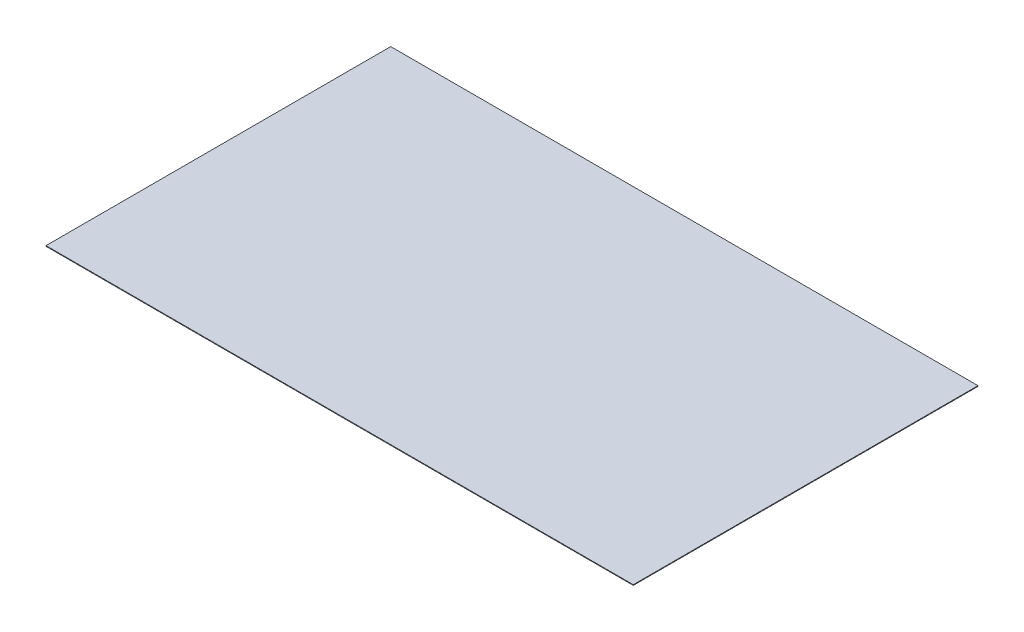
SolidWorks part; units mm, degrees
ref_plane "Front Plane" through (0, 0, 0) normal (0, 0, 1) x (1, 0, 0)
ref_plane "Top Plane" through (0, 0, 0) normal (0, 1, 0) x (1, 0, 0)
ref_plane "Right Plane" through (0, 0, 0) normal (1, 0, 0) x (0, 0, -1)
other "Configuration Table"
sketch "Sketch1" plane through (0, 0, 0) normal (0, 0, 1) x (1, 0, 0)
  line L1 (1.5, 1968.5) -> (1398.5, 1968.5)
  line L2 (1.5, 1968.5) -> (1.5, 1970)
  line L3 (1.5, 1970) -> (1398.5, 1970)
  line L4 (1398.5, 1968.5) -> (1398.5, 1970)
extrude "STORE_dis_ust_1" add sketch "Sketch1" against normal blind 820 separate body
